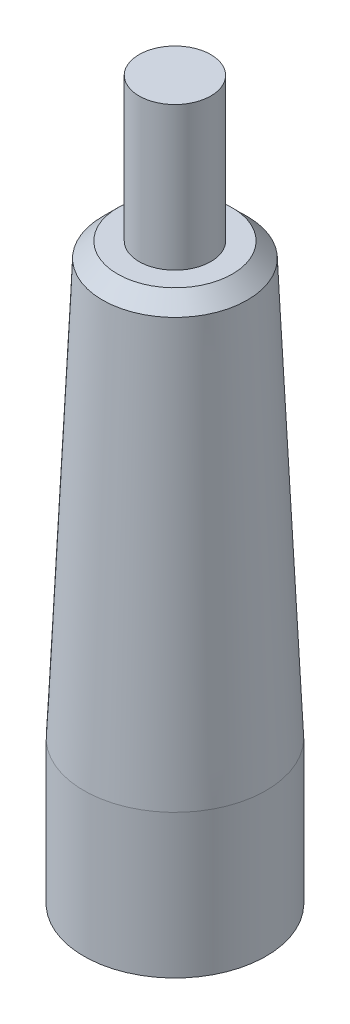
SolidWorks part; units mm, degrees
ref_plane "Front" through (0, 0, 0) normal (0, 0, 1) x (1, 0, 0)
ref_plane "Top" through (0, 0, 0) normal (0, 1, 0) x (1, 0, 0)
ref_plane "Right" through (0, 0, 0) normal (1, 0, 0) x (0, 0, -1)
sketch "Sketch4" plane through (0, 0, 0) normal (0, 0, 1) x (1, 0, 0)
  line L0 (0, 0) -> (0, 20)
  line L1 (0, 20) -> (2.5, 20) construction
  line L5 (3.175, 5) -> (3.175, 0)
  line L6 (3.175, 0) -> (0, 0)
  line L7 (2.5, 20) -> (3.175, 5)
  line L8 (0, 20) -> (0, 25)
  line L9 (0, 25) -> (1.25, 25)
  line L10 (1.25, 25) -> (1.25, 20)
  line L11 (1.25, 20) -> (2.5, 20)
  dimension "D1" = 20
  dimension "D2" = 2.5
  dimension "D3" = 5
  dimension "D4" = 5
  dimension "D5" = 1.25
  dimension "D6" = 3.175
revolve "Revolve1" add sketch "Sketch4" angle 360 about L0
sketch "Sketch6" plane through (0, 20, 0) normal (0, 1, 0) x (1, 0, 0)
  circle A0 centre (0, 0) radius 2
  circle A1 centre (0, 0) radius 3
  dimension "D1" = 4
  dimension "D2" = 6
extrude "Cut-Extrude1" [suppressed] cut sketch "Sketch6" against normal blind 1
chamfer "Chamfer3" distance 0.5 angle 45 1 edges at (0, 20, -2.5)
